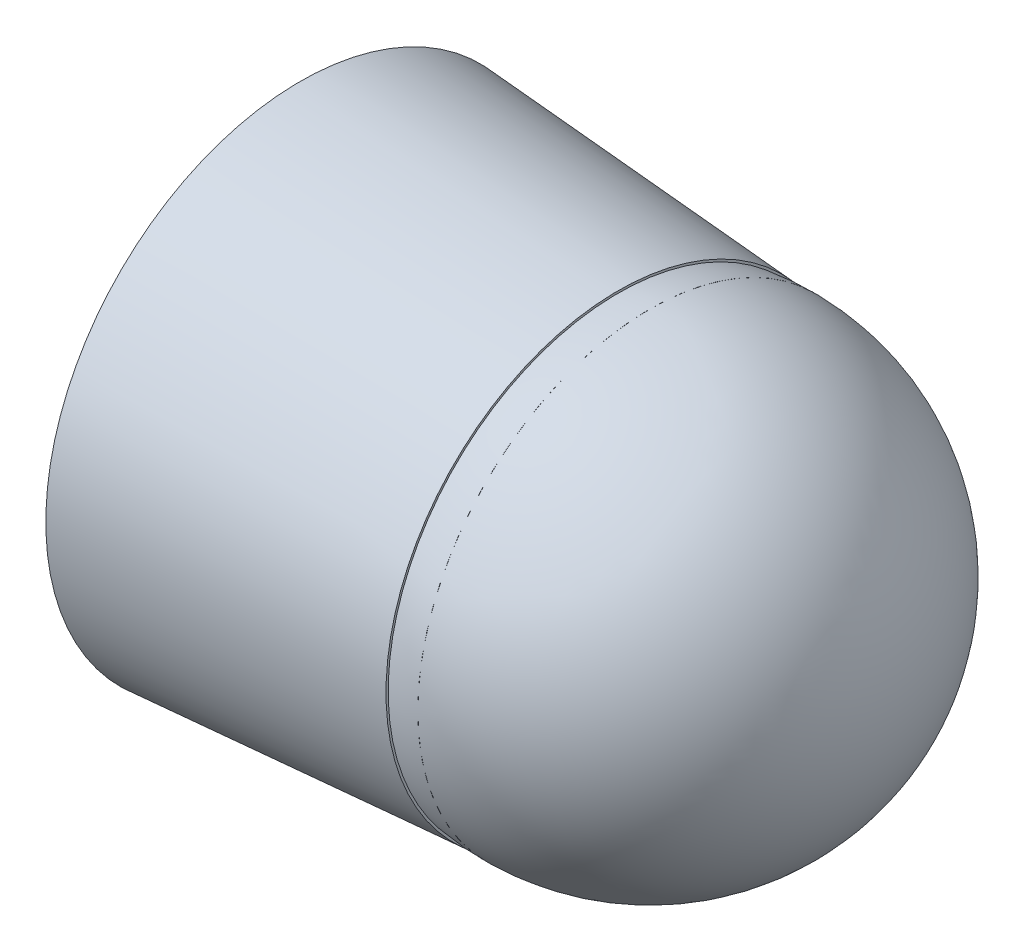
SolidWorks part; units mm, degrees
ref_plane "Front Plane" through (0, 0, 0) normal (0, 0, 1) x (1, 0, 0)
ref_plane "Top Plane" through (0, 0, 0) normal (0, 1, 0) x (1, 0, 0)
ref_plane "Right Plane" through (0, 0, 0) normal (1, 0, 0) x (0, 0, -1)
sketch "Sketch1" plane through (0, 0, 0) normal (1, 0, 0) x (0, 0, -1)
  circle A0 centre (0, 0) radius 8
  dimension "D1" = 16
extrude "Boss-Extrude1" add sketch "Sketch1" along normal blind 10 draft 4
surface "Surface-Offset1" parameters "D1"=1
sketch "Sketch2" plane through (11, 0, 0) normal (1, 0, 0) x (0, 0, -1)
  line L0 (0, 7.3007) -> (0, -7.3007) construction
  line L1 (0, 7.3007) -> (0, -7.3007)
  arc A0 (0, -7.3007) -> (0, 7.3007) centre (0, 0) ccw
  circle A1 centre (0, 0) radius 7.3007 construction
  dimension "D1" = 7.3007
revolve "Revolve1" add sketch "Sketch2" angle 360 about L0
